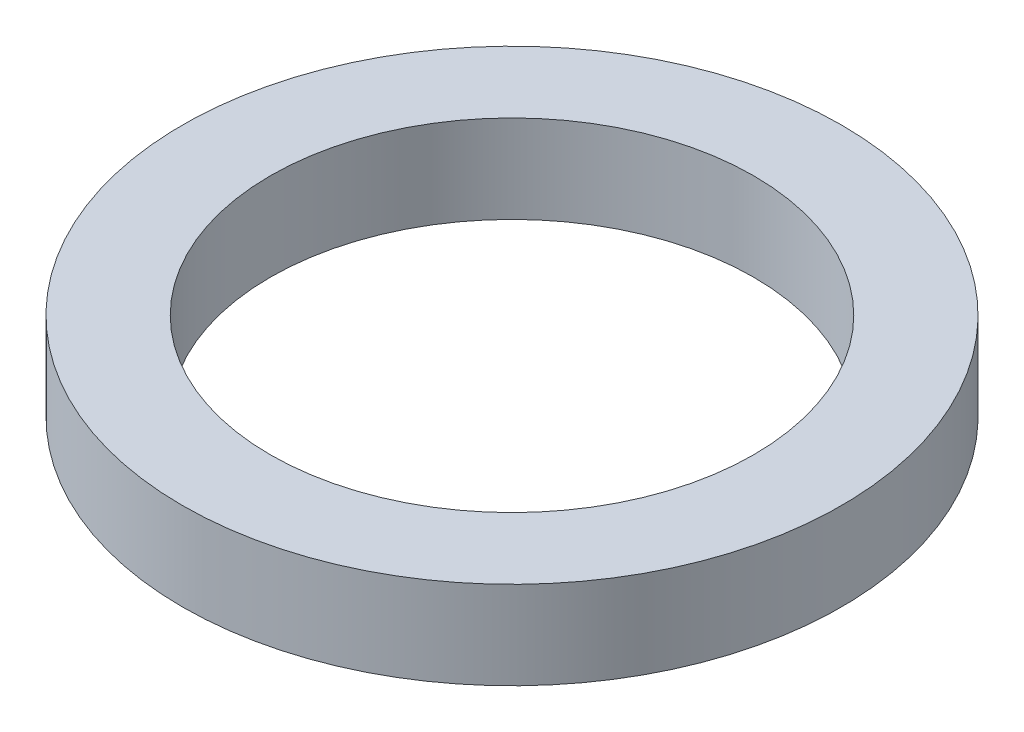
SolidWorks part; units mm, degrees
material "AISI 类型 A2 刀具钢"
ref_plane "前视基准面" through (0, 0, 0) normal (0, 0, 1) x (1, 0, 0)
ref_plane "上视基准面" through (0, 0, 0) normal (0, 1, 0) x (1, 0, 0)
ref_plane "右视基准面" through (0, 0, 0) normal (1, 0, 0) x (0, 0, -1)
sketch "草图1" plane through (0, 0, 0) normal (0, 1, 0) x (1, 0, 0)
  circle A0 centre (0, 0) radius 7.5
  circle A1 centre (0, 0) radius 5.5
  dimension "D1" = 15
  dimension "D2" = 11
extrude "凸台-拉伸1" add sketch "草图1" along normal blind 2
